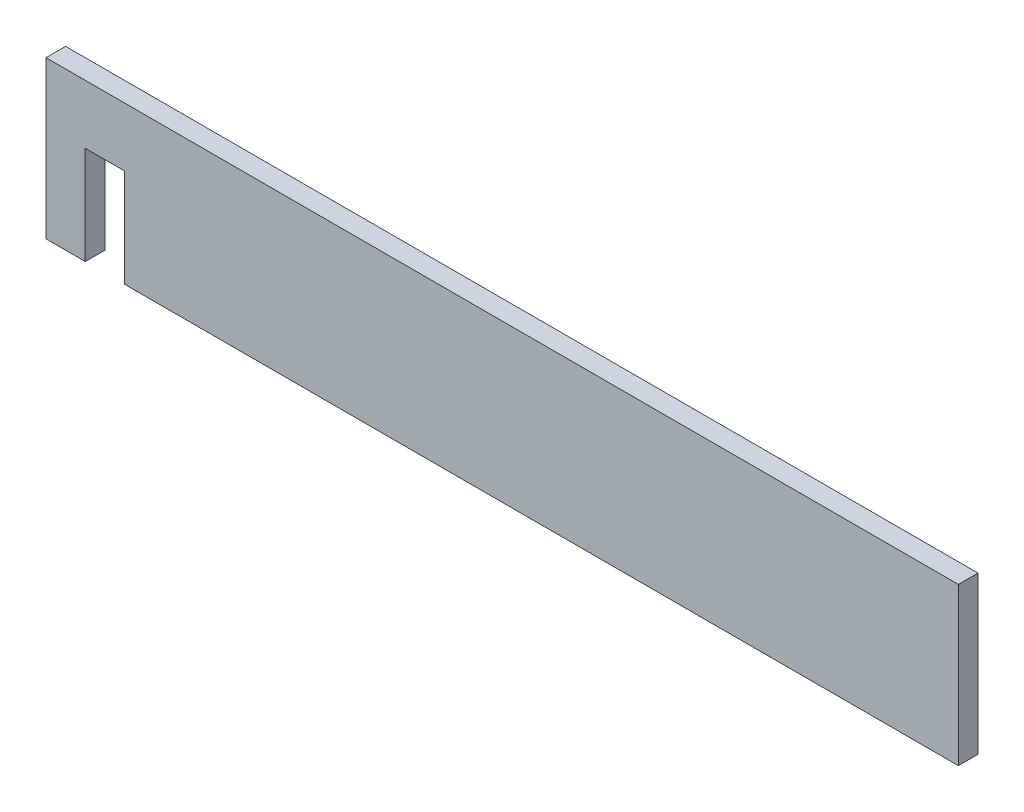
SolidWorks part; units mm, degrees
ref_plane "Front" through (0, 0, 0) normal (0, 0, 1) x (1, 0, 0)
ref_plane "Top" through (0, 0, 0) normal (0, 1, 0) x (1, 0, 0)
ref_plane "Right" through (0, 0, 0) normal (1, 0, 0) x (0, 0, -1)
sketch "Sketch1" plane through (0, 0, 0) normal (0, 0, 1) x (1, 0, 0)
  line L0 (10.16, 0) -> (118.11, 0)
  line L1 (0, 0) -> (5.08, 0)
  line L2 (0, 0) -> (0, 20.32)
  line L3 (0, 20.32) -> (118.11, 20.32)
  line L4 (118.11, 0) -> (118.11, 20.32)
  line L6 (5.08, 0) -> (5.08, 12.7)
  line L7 (5.08, 12.7) -> (10.16, 12.7)
  line L8 (10.16, 0) -> (10.16, 12.7)
  dimension "D1" = 20.32
  dimension "D2" = 118.11
  dimension "D3" = 5.08
  dimension "D4" = 12.7
  dimension "D5" = 5.08
extrude "Boss-Extrude1" add sketch "Sketch1" along normal blind 2.54
